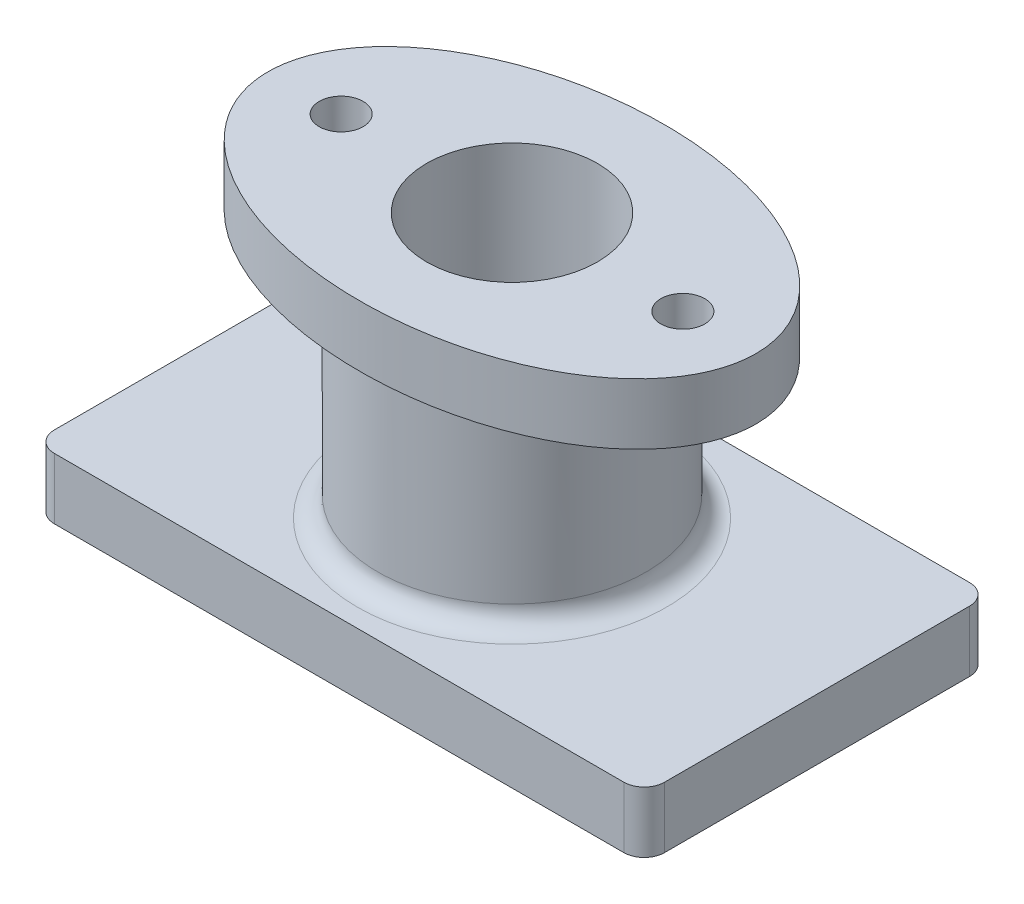
SolidWorks part; units mm, degrees
ref_plane "前视基准面" through (0, 0, 0) normal (0, 0, 1) x (1, 0, 0)
ref_plane "上视基准面" through (0, 0, 0) normal (0, 1, 0) x (1, 0, 0)
ref_plane "右视基准面" through (0, 0, 0) normal (1, 0, 0) x (0, 0, -1)
other "Configuration Table"
sketch "草图1" plane through (0, 0, 0) normal (0, 1, 0) x (1, 0, 0)
  line L1 (-70, -42.5) -> (70, -42.5)
  line L2 (-75, -37.5) -> (-75, 37.5)
  line L3 (-70, 42.5) -> (70, 42.5)
  line L4 (75, -37.5) -> (75, 37.5)
  line L5 (-75, -42.5) -> (75, 42.5) construction
  line L6 (-75, 42.5) -> (75, -42.5) construction
  arc A0 (-70, -42.5) -> (-75, -37.5) centre (-70, -37.5) cw
  arc A1 (70, -42.5) -> (75, -37.5) centre (70, -37.5) ccw
  arc A2 (70, 42.5) -> (75, 37.5) centre (70, 37.5) cw
  arc A3 (-75, 37.5) -> (-70, 42.5) centre (-70, 37.5) cw
  point P0 (0, 0)
  dimension "D3" = 5
  dimension "D1" = 85
  dimension "D2" = 150
extrude "凸台-拉伸1" add sketch "草图1" along normal blind 15
sketch "草图2" plane through (0, 15, 0) normal (0, 1, 0) x (1, 0, 0)
  circle A0 centre (0, 0) radius 33
  dimension "D1" = 66
extrude "凸台-拉伸2" add sketch "草图2" along normal blind 50
sketch "草图3" plane through (0, 65, 0) normal (0, 1, 0) x (1, 0, 0)
  line L0 (0, 0) -> (60, 0) construction
  line L1 (0, 0) -> (0, 37.5) construction
  ellipse E0 centre (0, 0) end of major axis (60, 0) minor radius 37.5
  dimension "D1" = 75
  dimension "D2" = 120
extrude "凸台-拉伸3" add sketch "草图3" along normal blind 15
sketch "草图4" plane through (0, 80, 0) normal (0, 1, 0) x (1, 0, 0)
  circle A0 centre (0, 0) radius 21
  dimension "D1" = 42
extrude "切除-拉伸1" cut sketch "草图4" against normal blind 65
sketch "草图5" plane through (0, 0, 0) normal (0, -1, 0) x (1, 0, 0)
  circle A0 centre (0, 0) radius 16.5
  dimension "D1" = 33
extrude "切除-拉伸2" cut sketch "草图5" against normal up to next
sketch "草图6" plane through (0, 80, 0) normal (0, 1, 0) x (1, 0, 0)
  line L0 (0, 0) -> (42, 0) construction
  line L1 (0, 0) -> (0, 30.2872) construction
  circle A0 centre (42, 0) radius 5.4
  circle A1 centre (-42, 0) radius 5.4
  dimension "D1" = 10.8
  dimension "D2" = 84
extrude "切除-拉伸3" cut sketch "草图6" against normal up to next
cosmetic thread "装饰螺纹线3" parameters "D2"=12
cosmetic thread "装饰螺纹线4" parameters "D2"=12
fillet "圆角1" radius 5 1 edges at (0, 15, -33)
